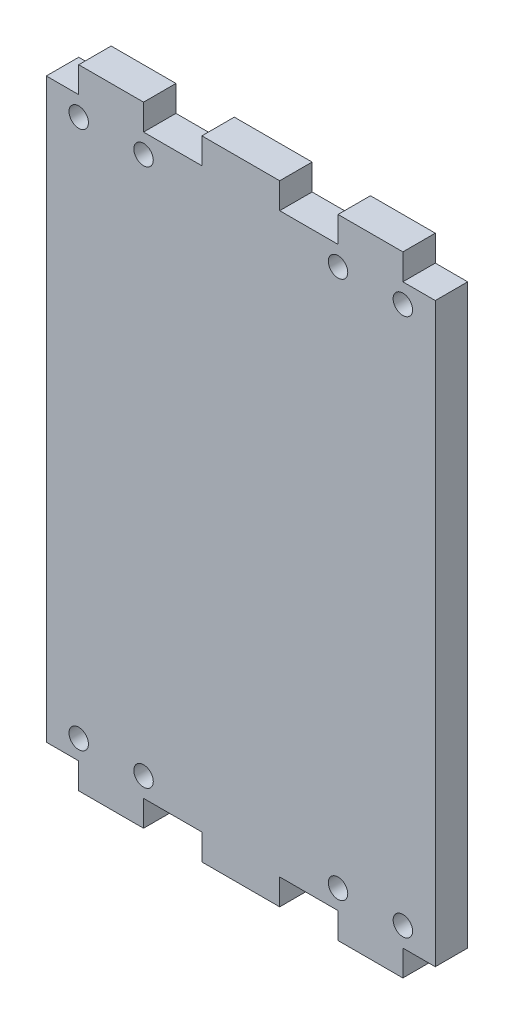
SolidWorks part; units mm, degrees
material "6061 合金"
ref_plane "前视基准面" through (0, 0, 0) normal (0, 0, 1) x (1, 0, 0)
ref_plane "上视基准面" through (0, 0, 0) normal (0, 1, 0) x (1, 0, 0)
ref_plane "右视基准面" through (0, 0, 0) normal (1, 0, 0) x (0, 0, -1)
other "Configuration Table"
sketch "草图1" plane through (0, 0, 0) normal (0, 0, 1) x (1, 0, 0)
  line L1 (-30, 48.5) -> (30, 48.5)
  line L2 (-30, 48.5) -> (-30, -48.5)
  line L3 (-30, -48.5) -> (30, -48.5)
  line L4 (30, 48.5) -> (30, -48.5)
  line L5 (-30, 48.5) -> (30, -48.5) construction
  line L6 (-30, -48.5) -> (30, 48.5) construction
  point P0 (0, 0)
  dimension "D1" = 97
  dimension "D2" = 60
extrude "凸台-拉伸1" add sketch "草图1" along normal blind 5
sketch "草图2" plane through (0, 0, 5) normal (0, 0, 1) x (1, 0, 0)
  line L0 (0, 0) -> (0, 50000) construction
  line L1 (6, 48.5) -> (-6, 48.5)
  line L2 (30, 48.5) -> (-30, 48.5) construction
  line L3 (-6, 48.5) -> (-6, 44.5)
  line L5 (6, 44.5) -> (6, 48.5)
  line L6 (-6, 44.5) -> (-15, 44.5)
  line L7 (-15, 44.5) -> (-15, 48.5)
  line L8 (-15, 48.5) -> (-25, 48.5)
  line L9 (-25, 48.5) -> (-25, 44.5)
  line L10 (-25, 44.5) -> (-30, 44.5)
  line L11 (-30, 48.5) -> (-30, -48.5) construction
  line L12 (6, 44.5) -> (15, 44.5)
  line L13 (15, 44.5) -> (15, 48.5)
  line L14 (15, 48.5) -> (25, 48.5)
  line L15 (25, 48.5) -> (25, 44.5)
  line L16 (25, 44.5) -> (30, 44.5)
  line L17 (30, -48.5) -> (30, 48.5) construction
  line L18 (0, 0) -> (-50000, 0) construction
  line L19 (25, -44.5) -> (30, -44.5)
  line L20 (25, -48.5) -> (25, -44.5)
  line L21 (15, -48.5) -> (25, -48.5)
  line L22 (15, -44.5) -> (15, -48.5)
  line L23 (6, -44.5) -> (15, -44.5)
  line L24 (-25, -44.5) -> (-30, -44.5)
  line L25 (-25, -48.5) -> (-25, -44.5)
  line L26 (-15, -48.5) -> (-25, -48.5)
  line L27 (-15, -44.5) -> (-15, -48.5)
  line L28 (-6, -44.5) -> (-15, -44.5)
  line L29 (6, -44.5) -> (6, -48.5)
  line L30 (-6, -48.5) -> (-6, -44.5)
  line L31 (6, -48.5) -> (-6, -48.5)
  line L32 (-30, -44.5) -> (-30, 44.5)
  line L33 (30, 44.5) -> (30, -44.5)
  point P8 (0, 48.5)
  point P40 (0, -48.5)
  dimension "D1" = 6
  dimension "D2" = 12
  dimension "D3" = 4
  dimension "D4" = 10
  dimension "D5" = 9
  dimension "D6" = 9
  dimension "D7" = 10
extrude "切除-拉伸1" cut sketch "草图2" against normal blind 10 flip side to cut
sketch "草图3" plane through (0, 0, 5) normal (0, 0, 1) x (1, 0, 0)
  line L0 (-30, 44.5) -> (-30, -44.5) construction
  line L1 (45, 44.5) -> (-45, 44.5) construction
  line L2 (0, 0) -> (0, 50000) construction
  line L3 (0, 0) -> (-50000, 0) construction
  circle A0 centre (-25, 41.5) radius 1.5
  circle A1 centre (-15, 41.505) radius 1.5
  circle A2 centre (15, 41.505) radius 1.5
  circle A3 centre (25, 41.5) radius 1.5
  circle A4 centre (25, -41.5) radius 1.5
  circle A5 centre (15, -41.505) radius 1.5
  circle A6 centre (-15, -41.505) radius 1.5
  circle A7 centre (-25, -41.5) radius 1.5
  dimension "D1" = 3
  dimension "D2" = 3
  dimension "D3" = 10
  dimension "D4" = 5
  dimension "D5" = 3
extrude "切除-拉伸2" cut sketch "草图3" against normal blind 10
